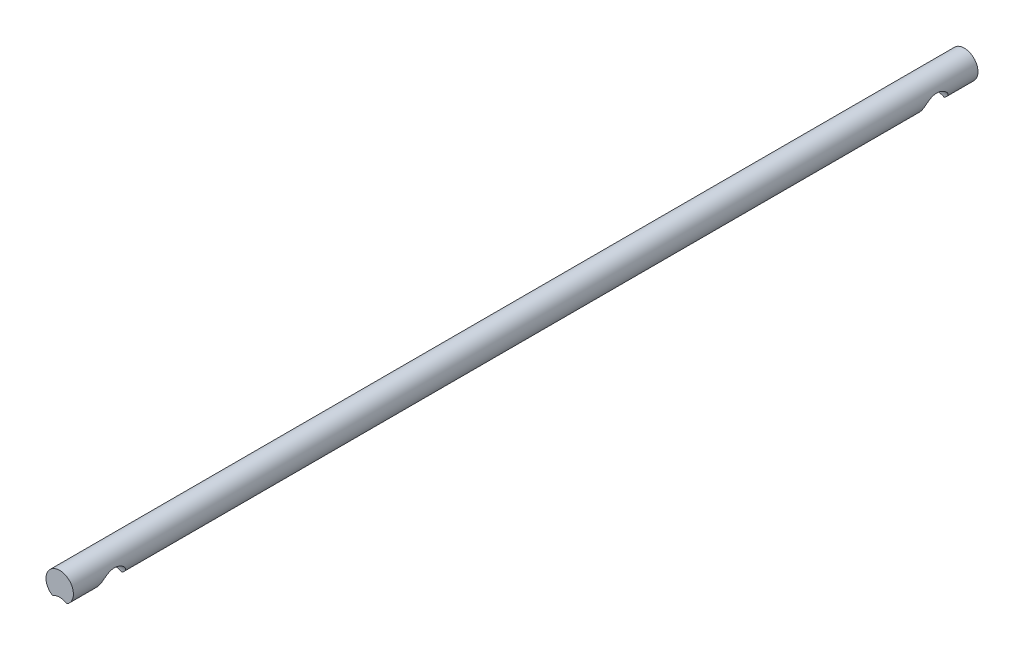
SolidWorks part; units mm, degrees
ref_plane "Спереди" through (0, 0, 0) normal (0, 0, 1) x (1, 0, 0)
ref_plane "Сверху" through (0, 0, 0) normal (0, 1, 0) x (1, 0, 0)
ref_plane "Справа" through (0, 0, 0) normal (1, 0, 0) x (0, 0, -1)
sketch "Эскиз1" plane through (0, 0, 0) normal (0, 0, 1) x (1, 0, 0)
  line L0 (0, 100) -> (0, -70) construction
  circle A0 centre (0, 0) radius 100
  circle A2 centre (0, -175) radius 105
  point P6 (0, 0)
  dimension "D1" = 200
  dimension "D3" = 210
  dimension "D2" = 170
extrude "Бобышка-Вытянуть1" add sketch "Эскиз1" along normal mid plane 6600 contours L0 A0 A2 | A0 L0 A2
sketch "Эскиз2" plane through (0, 0, 0) normal (1, 0, 0) x (0, 0, -1)
  line L0 (-3300, 100) -> (-3300, -84.5714) construction
  line L1 (-3300, -84.5714) -> (3300, -84.5714) construction
  line L2 (0, 0) -> (0, 114.413) construction
  circle A0 centre (-3000, -84.5714) radius 100
  circle A1 centre (3000, -84.5714) radius 100
  dimension "D2" = 200
  dimension "D1" = 300
extrude "Вырез-Вытянуть1" cut sketch "Эскиз2" against normal mid plane 6000
sketch "Эскиз3" plane through (0, 0, 0) normal (0, 1, 0) x (1, 0, 0)
  line L0 (-100, -3300) -> (100, -3300) construction
  line L1 (0, -2920.923) -> (0, -3079.077) construction
  line L2 (-79.077, -3000) -> (79.077, -3000) construction
  line L3 (0, 0) -> (163.9977, 0) construction
  line L4 (-79.077, 3000) -> (79.077, 3000) construction
  line L5 (0, 2920.923) -> (0, 3079.077) construction
  circle A0 centre (0, -3000) radius 79.077 construction
  circle A1 centre (0, 3000) radius 79.077 construction
  dimension "D2" = 158.1541
  dimension "D1" = 300
equation "\"Длина\"= 6000 + 600"
equation "\"D1@Бобышка-Вытянуть1\"=\"Длина\""
